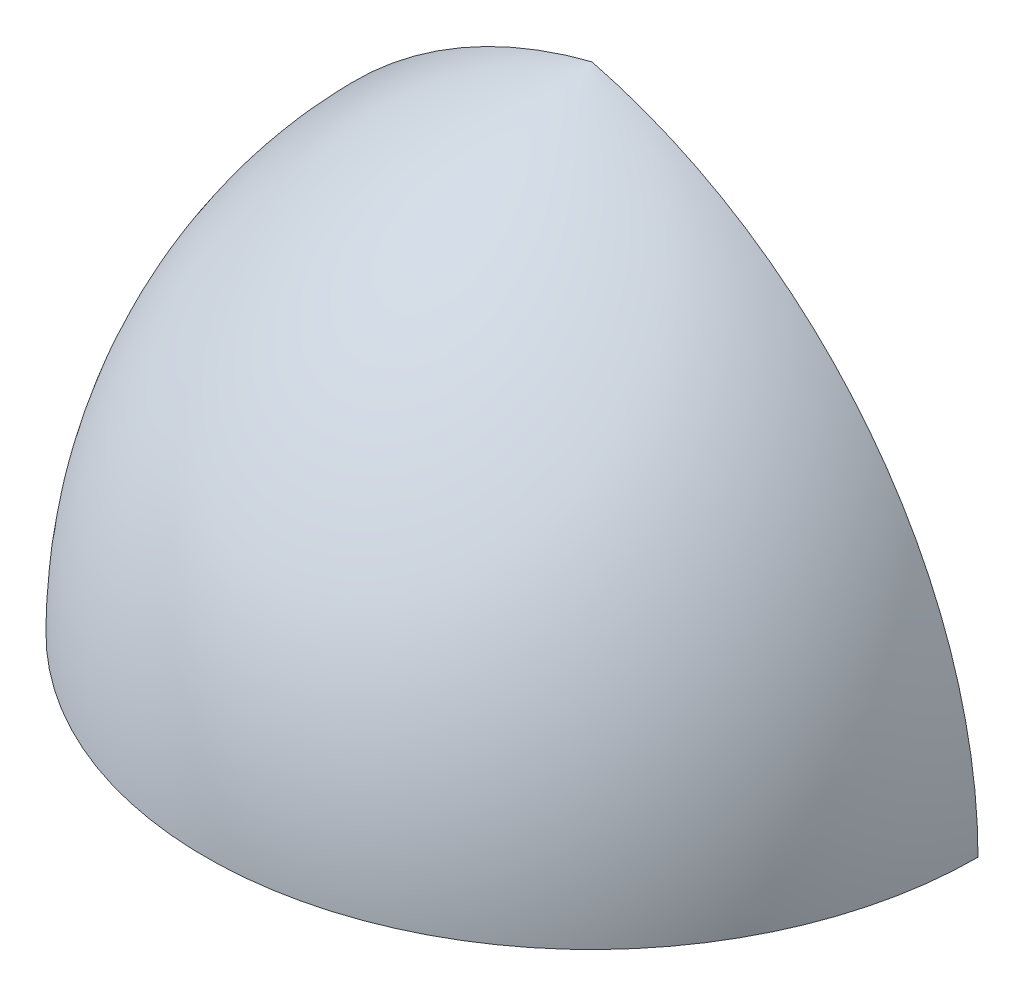
SolidWorks part; units mm, degrees
ref_plane "Front Plane" through (0, 0, 0) normal (0, 0, 1) x (1, 0, 0)
ref_plane "Top Plane" through (0, 0, 0) normal (0, 1, 0) x (1, 0, 0)
ref_plane "Right Plane" through (0, 0, 0) normal (1, 0, 0) x (0, 0, -1)
sketch "Sketch1" plane through (0, 0, 0) normal (0, 0, 1) x (1, 0, 0)
  line L0 (0, 0) -> (0, 388.5)
  line L1 (0, 0) -> (-302.5, 0)
  arc A0 (-302.5, 0) -> (0, 388.5) centre (98.2248, 0) cw
  dimension "D1" = 388.5
  dimension "D2" = 302.5
revolve "Revolve3" add sketch "Sketch1" angle 180 about L0
